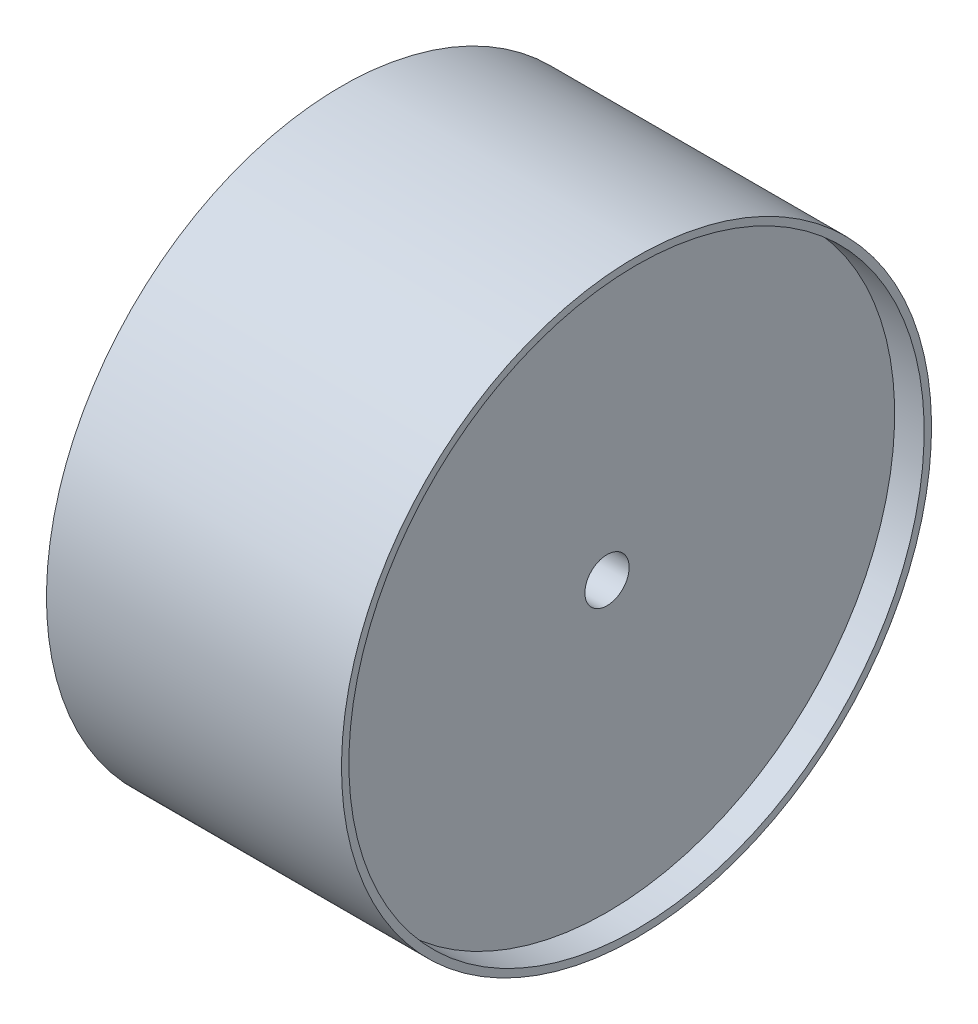
SolidWorks part; units mm, degrees
ref_plane "Спереди" through (0, 0, 0) normal (0, 0, 1) x (1, 0, 0)
ref_plane "Сверху" through (0, 0, 0) normal (0, 1, 0) x (1, 0, 0)
ref_plane "Справа" through (0, 0, 0) normal (1, 0, 0) x (0, 0, -1)
sketch "Эскиз1" plane through (0, 0, 0) normal (0, 0, 1) x (1, 0, 0)
  line L0 (-40, 80) -> (40, 80)
  line L1 (40, 80) -> (40, 78)
  line L2 (40, 78) -> (32, 78)
  line L3 (32, 78) -> (32, 6)
  line L4 (-32, 78) -> (-32, 6)
  line L5 (0, 0) -> (0, -75.9673) construction
  line L6 (-40, 78) -> (-32, 78)
  line L7 (-40, 80) -> (-40, 78)
  line L8 (-118.1796, 0) -> (197.0213, 0) construction
  line L9 (32, 6) -> (30, 6)
  line L10 (30, 8) -> (30, 78)
  line L11 (30, 78) -> (-30, 78)
  line L12 (-32, 6) -> (-30, 6)
  line L13 (-30, 8) -> (-30, 78)
  line L14 (-30, 8) -> (30, 8)
  line L15 (-30, 6) -> (30, 6)
  point P5 (0, 80)
  point P13 (0, 80)
  point P21 (0, 78)
  dimension "D1" = 80
  dimension "D2" = 40
  dimension "D3" = 2
  dimension "D4" = 8
  dimension "D5" = 6
  dimension "D6" = 2
  dimension "D7" = 2
revolve "Повернуть1" add sketch "Эскиз1" angle 360 about L8
sketch "Эскиз3" plane through (-32, 0, 0) normal (-1, 0, 0) x (0, 0, 1)
  circle A0 centre (0, -49.9848) radius 7.5
  dimension "D1" = 15
extrude "Вырез-Вытянуть1" cut sketch "Эскиз3" against normal blind 17
